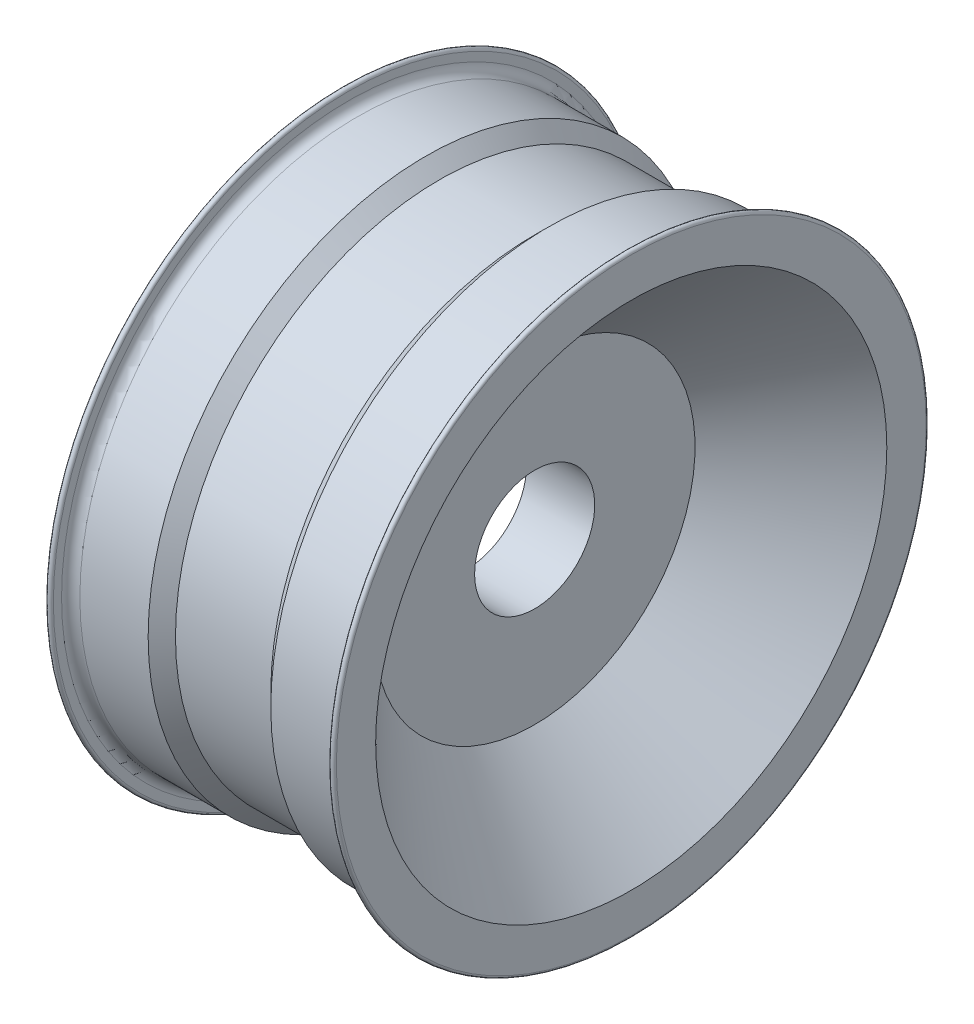
SolidWorks part; units mm, degrees
ref_plane "Front Plane" through (0, 0, 0) normal (0, 0, 1) x (1, 0, 0)
ref_plane "Top Plane" through (0, 0, 0) normal (0, 1, 0) x (1, 0, 0)
ref_plane "Right Plane" through (0, 0, 0) normal (1, 0, 0) x (0, 0, -1)
sketch "Sketch1" plane through (0, 0, 0) normal (0, 0, 1) x (1, 0, 0)
  line L0 (0, 0) -> (34.9, 0)
  line L2 (141.8707, -423.1531) -> (213.0756, -351.9482)
  line L4 (0, 0) -> (0, 117.432)
  line L5 (0, 117.432) -> (-105.6, 188.495)
  line L7 (101.6, 215.9) -> (101.6, 209.9)
  line L8 (94.9, 203.2) -> (44.9, 203.2)
  line L9 (44.9, 203.2) -> (34.9, 193.2)
  line L10 (34.9, 193.2) -> (-34.9, 193.2)
  line L11 (-34.9, 193.2) -> (-44.9, 203.2)
  line L14 (0, 117.432) -> (0, 126.938) construction
  line L16 (-44.9, 203.2) -> (-94.9, 203.2)
  line L17 (-105.6, 188.495) -> (-105.6, 215.9)
  line L18 (-101.6, 209.9) -> (-101.6, 215.9)
  line L19 (34.9, 0) -> (34.9, 117.432)
  line L20 (34.9, 117.432) -> (105.6, 187.1326)
  line L21 (105.6, 215.9) -> (105.6, 187.1326)
  line L22 (0, 0) -> (34.9, 0)
  arc A0 (105.6, 215.9) -> (101.6, 215.9) centre (103.6, 215.9) ccw
  arc A3 (101.6, 209.9) -> (94.9, 203.2) centre (94.9, 209.9) cw
  arc A4 (-105.6, 215.9) -> (-101.6, 215.9) centre (-103.6, 215.9) cw
  arc A5 (-94.9, 203.2) -> (-101.6, 209.9) centre (-94.9, 209.9) cw
  point P23 (-101.6, 203.2)
  dimension "D2" = 2
  dimension "D3" = 10
  dimension "D4" = 6.7
  dimension "D5" = 2
  dimension "D11" = 6.7
  dimension "D1" = 34.9
  dimension "D6" = 6
  dimension "D7" = 10
  dimension "D8" = 6
  dimension "D9" = 34.9
  dimension "D10" = 10
  dimension "D12" = 94.9
  dimension "D13" = 94.9
  dimension "D14" = 34.9
  dimension "D15" = 215.9
  dimension "D16" = 215.9
revolve "Revolve1" add sketch "Sketch1" angle 360 about L0
sketch "Sketch3" plane through (0, 0, 0) normal (-1, 0, 0) x (0, 0, 1)
  circle A0 centre (0, 0) radius 60
  circle A1 centre (0, 0) radius 43.9793
extrude "Boss-Extrude1" add sketch "Sketch3" along normal blind 15 contours A0 | A1
sketch "Sketch4" plane through (0, 0, 0) normal (-1, 0, 0) x (0, 0, 1)
  circle A0 centre (0, 0) radius 43.9793
extrude "Cut-Extrude1" cut sketch "Sketch4" against normal through all
